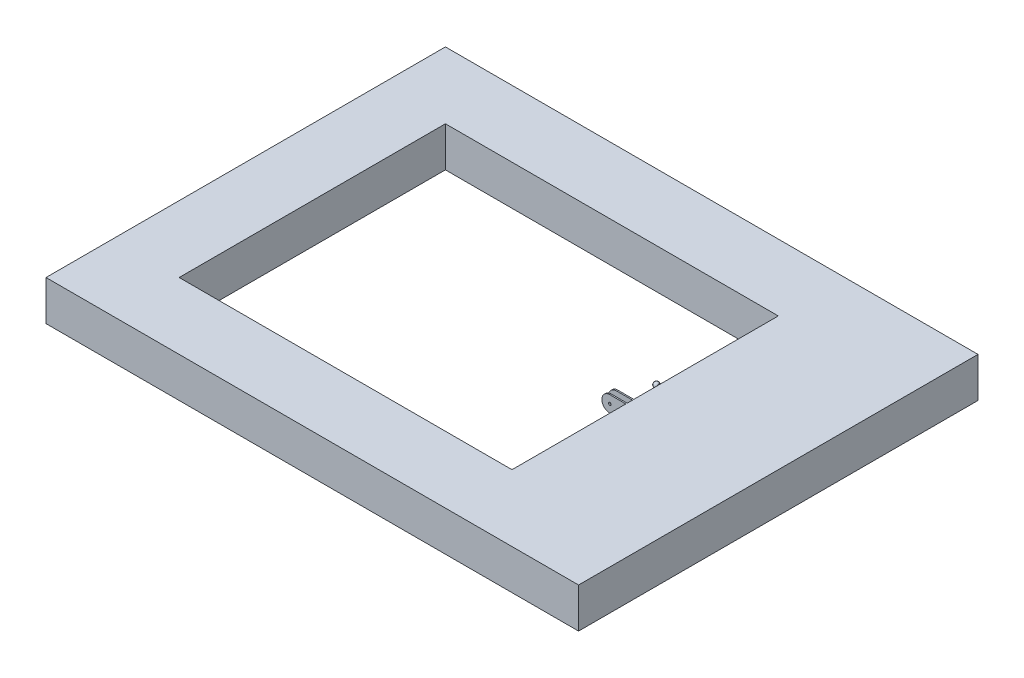
SolidWorks part; units mm, degrees
ref_plane "Front Plane" through (0, 0, 0) normal (0, 0, 1) x (1, 0, 0)
ref_plane "Top Plane" through (0, 0, 0) normal (0, 1, 0) x (1, 0, 0)
ref_plane "Right Plane" through (0, 0, 0) normal (1, 0, 0) x (0, 0, -1)
sketch "Sketch1" plane through (0, 0, 0) normal (0, 0, 1) x (1, 0, 0)
  line L1 (0, 0) -> (4000, 0)
  line L2 (0, 0) -> (0, 300)
  line L3 (0, 300) -> (4000, 300)
  line L4 (4000, 0) -> (4000, 300)
  dimension "D1" = 4000
  dimension "D2" = 300
extrude "Boss-Extrude1" add sketch "Sketch1" along normal blind 3000
sketch "Sketch3" plane through (0, 300, 0) normal (0, 1, 0) x (1, 0, 0)
  line L0 (0, -3000) -> (0, 0) construction
  line L1 (500, -500) -> (3000, -500)
  line L2 (500, -500) -> (500, -2500)
  line L3 (500, -2500) -> (3000, -2500)
  line L4 (3000, -500) -> (3000, -2500)
  line L5 (4000, -3000) -> (0, -3000) construction
  dimension "D1" = 2000
  dimension "D2" = 2500
  dimension "D3" = 500
  dimension "D4" = 500
extrude "Cut-Extrude1" cut sketch "Sketch3" against normal blind 3000
ref_plane "Plane2" through (0, 0, 1645) normal (0, 0, -1) x (-1, 0, 0)
sketch "Sketch6" plane through (0, 0, 1645) normal (0, 0, -1) x (-1, 0, 0)
  line L0 (-3000, 300) -> (-3000, 180)
  line L1 (-3000, 180) -> (-2880, 180)
  line L2 (-2880, 300) -> (-3000, 300)
  arc A0 (-2880, 180) -> (-2880, 300) centre (-2880, 240) ccw
  circle A1 centre (-2880, 240) radius 10
  dimension "D3" = 20
  dimension "D1" = 120
  dimension "D2" = 120
extrude "Boss-Extrude2" add sketch "Sketch6" along normal blind 10
ref_plane "Plane3" through (0, 0, 1595) normal (0, 0, -1) x (-1, 0, 0)
sketch "Sketch7" plane through (0, 0, 1595) normal (0, 0, -1) x (-1, 0, 0)
  line L0 (-3000, 300) -> (-3000, 180) construction
  line L1 (-3000, 180) -> (-2880, 180) construction
  line L2 (-2880, 300) -> (-3000, 300) construction
  line L3 (-3000, 300) -> (-3000, 180)
  line L4 (-3000, 180) -> (-2880, 180)
  line L5 (-2880, 300) -> (-3000, 300)
  circle A0 centre (-2880, 240) radius 10 construction
  arc A1 (-2880, 180) -> (-2880, 300) centre (-2880, 240) ccw construction
  circle A2 centre (-2880, 240) radius 10
  arc A3 (-2880, 180) -> (-2880, 300) centre (-2880, 240) ccw
extrude "Boss-Extrude3" add sketch "Sketch7" along normal blind 10
ref_plane "Plane4" through (0, 0, 1385) normal (0, 0, -1) x (-1, 0, 0)
sketch "Sketch8" plane through (0, 0, 1385) normal (0, 0, -1) x (-1, 0, 0)
  line L0 (-3000, 300) -> (-3000, 280)
  line L2 (-2986.0433, 291.9421) -> (-3000, 300)
  line L3 (-3000, 280) -> (-2950, 280)
  arc A0 (-2950, 280) -> (-2986.0433, 291.9421) centre (-2970, 280) ccw
  dimension "D4" = 20
  dimension "D3" = 50
  dimension "D1" = 60
  dimension "D2" = 20
revolve "Revolve1" add sketch "Sketch8" angle 360 about L3
